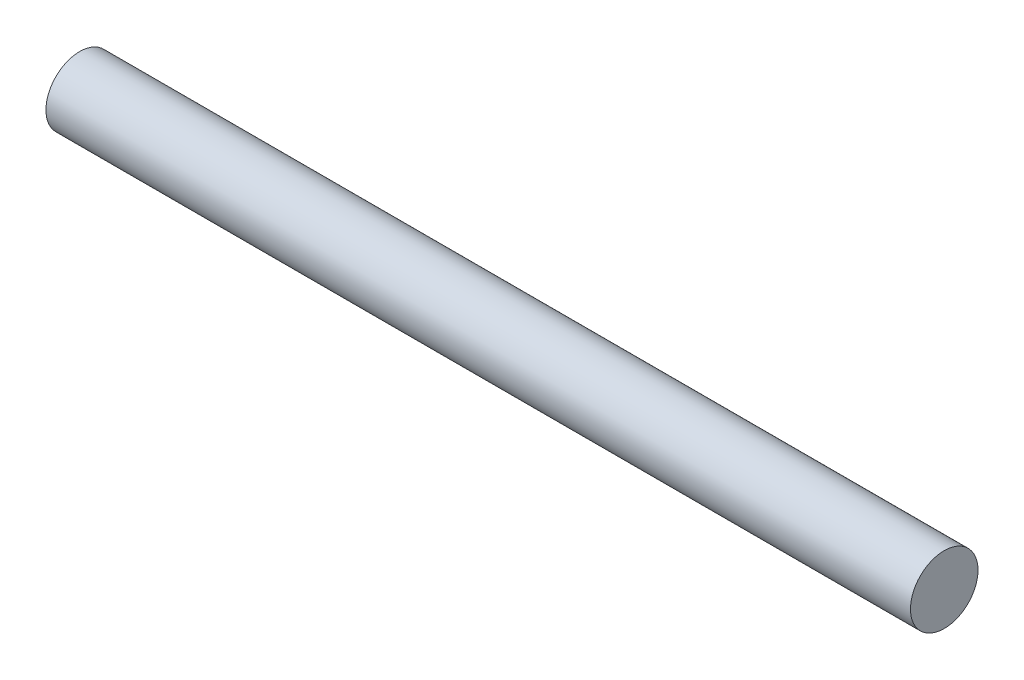
SolidWorks part; units mm, degrees
ref_plane "Front Plane" through (0, 0, 0) normal (0, 0, 1) x (1, 0, 0)
ref_plane "Top Plane" through (0, 0, 0) normal (0, 1, 0) x (1, 0, 0)
ref_plane "Right Plane" through (0, 0, 0) normal (1, 0, 0) x (0, 0, -1)
sketch "Sketch1" plane through (0, 0, 0) normal (1, 0, 0) x (0, 0, -1)
  circle A0 centre (0, 0) radius 2.5
  dimension "D1" = 5
extrude "Boss-Extrude1" add sketch "Sketch1" along normal blind 64
